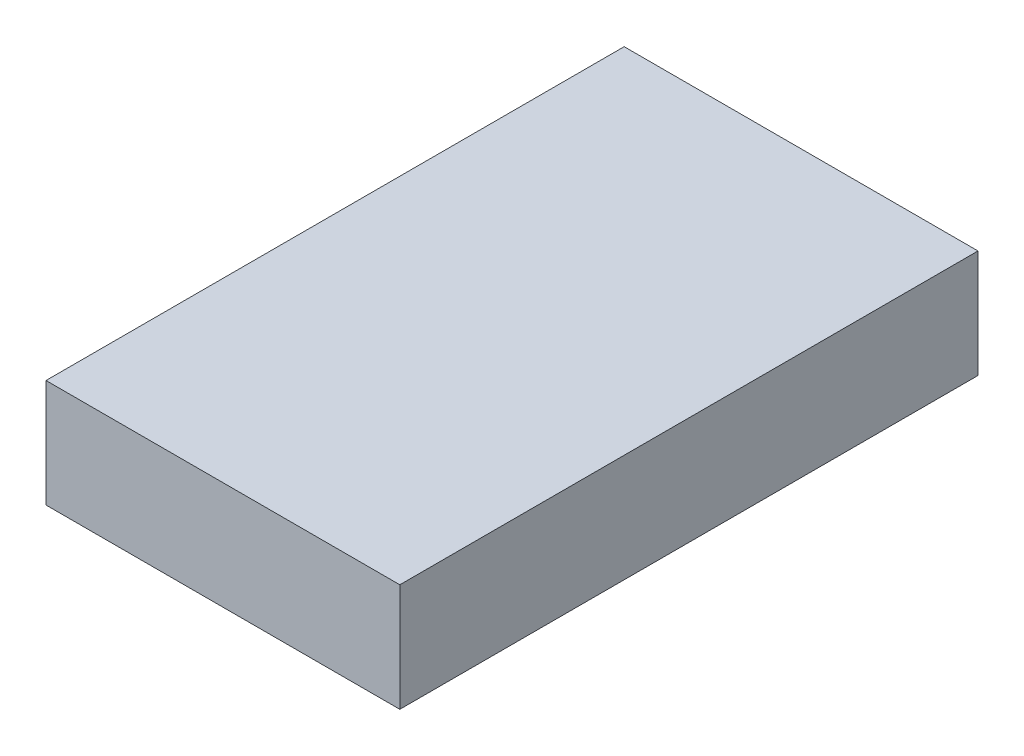
SolidWorks part; units mm, degrees
ref_plane "Front Plane" through (0, 0, 0) normal (0, 0, 1) x (1, 0, 0)
ref_plane "Top Plane" through (0, 0, 0) normal (0, 1, 0) x (1, 0, 0)
ref_plane "Right Plane" through (0, 0, 0) normal (1, 0, 0) x (0, 0, -1)
sketch "Sketch1" plane through (0, 0, 0) normal (0, 1, 0) x (1, 0, 0)
  line L1 (-41, 67) -> (41, 67)
  line L2 (-41, 67) -> (-41, -67)
  line L3 (-41, -67) -> (41, -67)
  line L4 (41, 67) -> (41, -67)
  line L5 (-41, 67) -> (41, -67) construction
  line L6 (-41, -67) -> (41, 67) construction
  point P0 (0, 0)
  dimension "D1" = 82
  dimension "D2" = 134
extrude "Boss-Extrude1" add sketch "Sketch1" along normal blind 25
